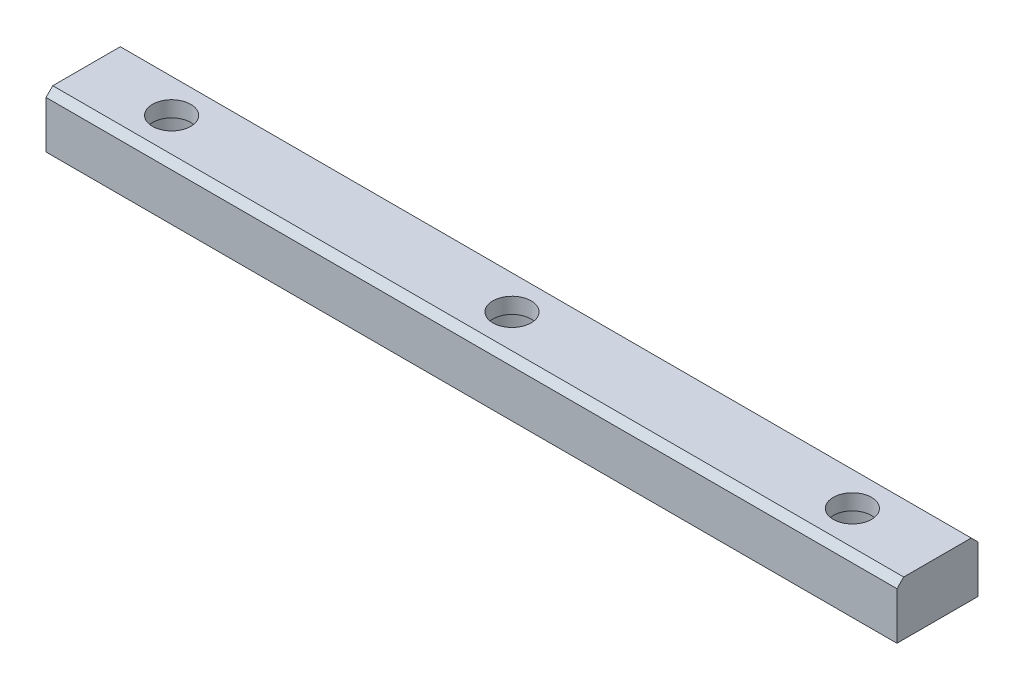
SolidWorks part; units mm, degrees
material "Low Carbon Steel"
ref_plane "Front Plane" through (0, 0, 0) normal (0, 0, 1) x (1, 0, 0)
ref_plane "Top Plane" through (0, 0, 0) normal (0, 1, 0) x (1, 0, 0)
ref_plane "Right Plane" through (0, 0, 0) normal (1, 0, 0) x (0, 0, -1)
sketch "Sketch1" plane through (0, 0, 0) normal (1, 0, 0) x (0, 0, -1)
  line L0 (-9.525, -6.35) -> (9.525, 6.35) construction
  line L1 (-9.525, 6.35) -> (9.525, 6.35)
  line L2 (-9.525, 6.35) -> (-9.525, -6.35)
  line L3 (-9.525, -6.35) -> (9.525, -6.35)
  line L4 (9.525, 6.35) -> (9.525, -6.35)
  dimension "D1" = 12.7
  dimension "D2" = 19.05
extrude "Boss-Extrude1" add sketch "Sketch1" along normal mid plane 200
hole_wizard "CBORE for M8 Hex Socket Head Cap Screw1" positions "Sketch3" profile "Sketch2" counterbore size "M8" standard "Peddi DIN" end condition through all
sketch "Sketch3" plane through (-66.3689, -6.35, -4.5401) normal (0, 1, 0) x (1, 0, 0)
  line L0 (-13.6311, -4.5401) -> (66.3689, -4.5401) construction
  line L1 (66.3689, -4.5401) -> (146.3689, -4.5401) construction
  point P0 (-13.6311, -4.5401)
  point P2 (66.3689, -4.5401)
  point P14 (146.3689, -4.5401)
  dimension "D1" = 80
sketch "Sketch2" plane through (-80, -6.35, 0) normal (1, 0, 0) x (0, 0, -1)
  line L0 (0, 0) -> (0, 12.7)
  line L1 (0, 12.7) -> (4.5, 12.7)
  line L3 (4.5, 12.7) -> (4.5, 9)
  line L4 (4.5, 9) -> (7.5, 9)
  line L5 (7.5, 9) -> (7.5, 0)
  line L7 (7.5, 0) -> (0, 0)
  line L11 (0, -6.35) -> (0, 107.95) construction
  dimension "Thru Hole Dia." = 9
  dimension "Thru Hole Depth" = 12.7
  dimension "C'Bore Dia." = 15
  dimension "C'Bore Depth" = 9
chamfer "Chamfer1" distance 1.5875 angle 45 2 edges at (0, 6.35, -9.525) (0, 6.35, 9.525)
other "Freeze***"
